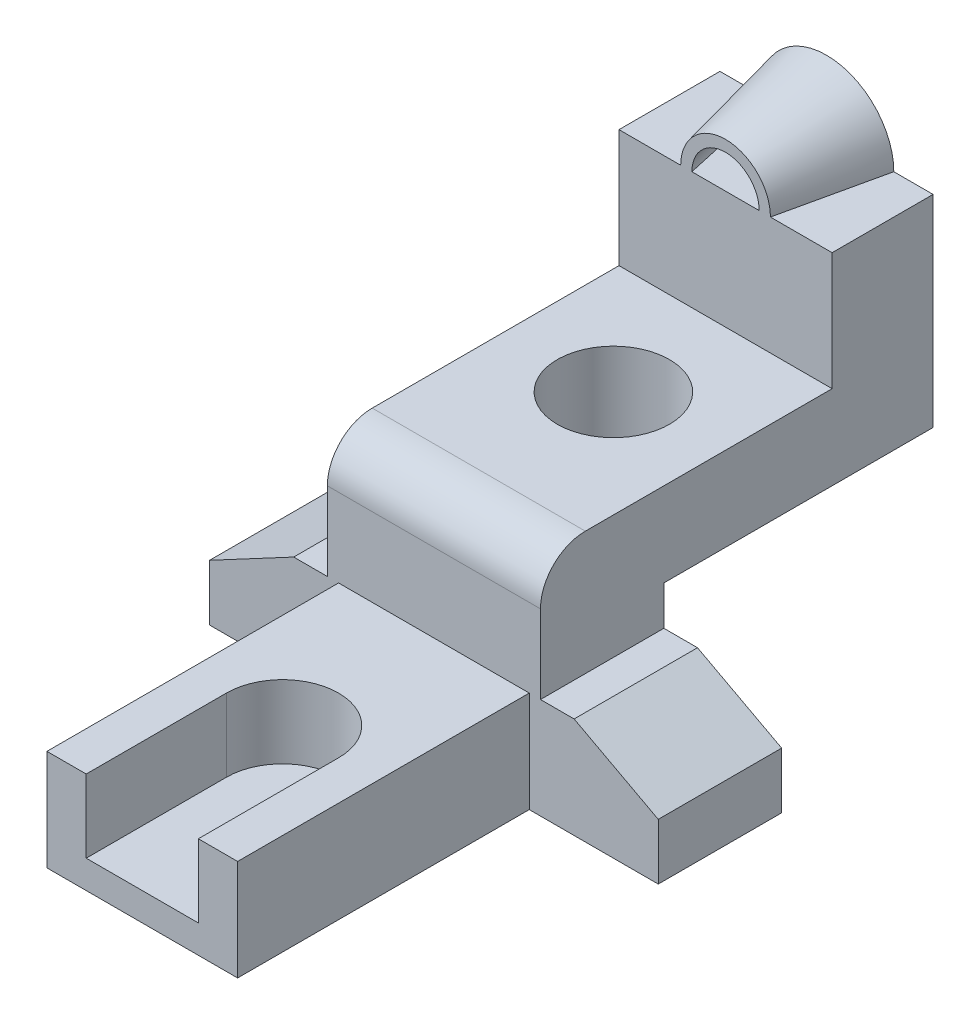
SolidWorks part; units mm, degrees
ref_plane "Front Plane" through (0, 0, 0) normal (0, 0, 1) x (1, 0, 0)
ref_plane "Top Plane" through (0, 0, 0) normal (0, 1, 0) x (1, 0, 0)
ref_plane "Right Plane" through (0, 0, 0) normal (1, 0, 0) x (0, 0, -1)
sketch "Sketch1" plane through (0, 0, 0) normal (1, 0, 0) x (0, 0, -1)
  line L0 (0, 0) -> (0, 40)
  line L1 (0, 40) -> (52, 40)
  line L2 (52, 40) -> (52, 61)
  line L3 (52, 61) -> (70, 61)
  line L4 (70, 61) -> (70, 25)
  line L5 (70, 25) -> (22, 25)
  line L6 (22, 25) -> (22, 0)
  line L7 (22, 0) -> (0, 0)
  dimension "D1" = 22
  dimension "D2" = 15
  dimension "D3" = 25
  dimension "D4" = 18
  dimension "D5" = 36
  dimension "D6" = 70
extrude "Boss-Extrude1" add sketch "Sketch1" along normal mid plane 80
sketch "Sketch2" plane through (0, 0, 0) normal (0, 0, 1) x (1, 0, 0)
  line L0 (0, 0) -> (0, 69.7137) construction
  line L1 (-40, 61) -> (-19, 61)
  line L2 (-40, 61) -> (-40, 18)
  line L3 (-40, 18) -> (-19, 18)
  line L4 (-19, 61) -> (-19, 18)
  line L5 (40, 61) -> (19, 61)
  line L6 (40, 61) -> (40, 18)
  line L7 (40, 18) -> (19, 18)
  line L8 (19, 61) -> (19, 18)
  line L9 (40, 0) -> (-40, 0) construction
  point P15 (-149.2944, 77.2411)
  point P16 (-143.7384, 93.0129)
  dimension "D1" = 38
  dimension "D2" = 18
extrude "Cut-Extrude1" cut sketch "Sketch2" against normal blind 80
sketch "Sketch3" plane through (0, 0, 0) normal (0, 0, 1) x (1, 0, 0)
  line L0 (25, 18) -> (40, 10)
  line L1 (19, 18) -> (40, 18) construction
  line L2 (40, 18) -> (40, 0) construction
  line L3 (40, 10) -> (40, 18)
  line L4 (40, 18) -> (25, 18)
  line L5 (40, 0) -> (-40, 0) construction
  dimension "D1" = 10
  dimension "D2" = 15
extrude "Cut-Extrude2" cut sketch "Sketch3" against normal blind 80
mirror "Mirror1" about plane through (0, 0, 0) normal (1, 0, 0) of "Cut-Extrude2"
sketch "Sketch4" plane through (0, 0, 0) normal (0, 0, 1) x (1, 0, 0)
  line L0 (40, 0) -> (-40, 0) construction
  line L1 (-17, 0) -> (17, 0)
  line L2 (-17, 0) -> (-17, 18)
  line L3 (-17, 18) -> (17, 18)
  line L4 (17, 0) -> (17, 18)
  line L5 (0, 0) -> (0, 26.4981) construction
  line L6 (19, 18) -> (25, 18) construction
  dimension "D1" = 34
extrude "Boss-Extrude3" add sketch "Sketch4" along normal blind 52
sketch "Sketch5" plane through (0, 18, 0) normal (0, 1, 0) x (1, 0, 0)
  line L0 (17, -52) -> (-17, -52) construction
  line L1 (-10, -27) -> (-10, -52)
  line L2 (-10, -52) -> (10, -52)
  line L3 (10, -52) -> (10, -27)
  arc A0 (10, -27) -> (-10, -27) centre (0, -27) ccw
  dimension "D1" = 20
  dimension "D2" = 25
extrude "Cut-Extrude3" cut sketch "Sketch5" against normal blind 13
sketch "Sketch6" plane through (0, 61, 0) normal (0, 1, 0) x (1, 0, 0)
  line L0 (6, 52) -> (10, 70)
  line L1 (19, 52) -> (-19, 52) construction
  line L2 (19, 70) -> (-19, 70) construction
  line L3 (10, 70) -> (12, 70)
  line L4 (12, 70) -> (8, 52)
  line L5 (8, 52) -> (6, 52)
  line L6 (0, 0) -> (0, 77.8348) construction
  dimension "D1" = 12
  dimension "D2" = 16
  dimension "D3" = 20
revolve "Revolve1" add sketch "Sketch6" angle 360 about L6
hole_wizard "Hole1" positions "Sketch7" profile "Sketch8" legacy end condition through all
sketch "Sketch7" plane through (0, 40, 0) normal (0, 1, 0) x (1, 0, 0)
  line L0 (19, 70) -> (12, 70) construction
  point P0 (0, 32)
  dimension "D1" = 38
sketch "Sketch8" plane through (0, 40, -32) normal (1, 0, 0) x (0, 0, 1)
  line L0 (0, 0) -> (0, 40)
  line L1 (0, 40) -> (10, 40)
  line L2 (10, 40) -> (10, 0)
  line L3 (10, 0) -> (0, 0)
  line L4 (0, 110) -> (0, -10) construction
  dimension "Diameter" = 20
  dimension "Depth" = 40
fillet "Fillet1" radius 8 1 edges at (0, 40, 0)
